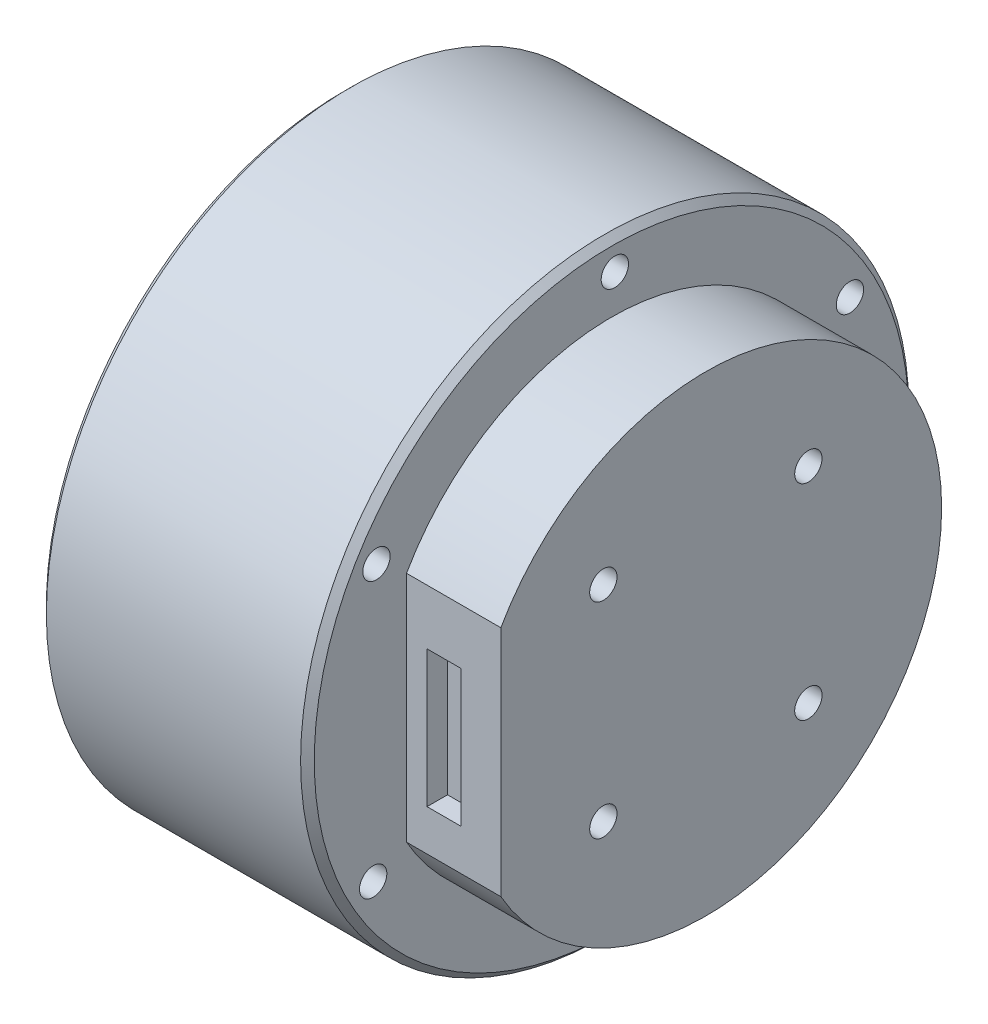
SolidWorks part; units mm, degrees
material "6061 合金"
ref_plane "前视基准面" through (0, 0, 0) normal (0, 0, 1) x (1, 0, 0)
ref_plane "上视基准面" through (0, 0, 0) normal (0, 1, 0) x (1, 0, 0)
ref_plane "右视基准面" through (0, 0, 0) normal (1, 0, 0) x (0, 0, -1)
other "Configuration Table"
sketch "草图1" plane through (0, 0, 0) normal (1, 0, 0) x (0, 0, -1)
  circle A0 centre (0, 0) radius 44.5
  dimension "D1" = 89
extrude "凸台-拉伸1" add sketch "草图1" along normal blind 39.2
sketch "草图2" plane through (39.2, 0, 0) normal (1, 0, 0) x (0, 0, -1)
  line L0 (-30, 17.0367) -> (-30, -17.0367)
  arc A0 (-30, -17.0367) -> (-30, 17.0367) centre (0, 0) ccw
  dimension "D1" = 69
  dimension "D2" = 30
extrude "凸台-拉伸3" add sketch "草图2" along normal blind 13.8
sketch "草图4" plane through (39.2, 0, 0) normal (1, 0, 0) x (0, 0, -1)
  circle A0 centre (0, 0) radius 40 construction
  circle A1 centre (0.4843, 39.9971) radius 2
  circle A2 centre (34.8806, 19.5791) radius 2
  circle A3 centre (34.3963, -20.418) radius 2
  circle A4 centre (-0.4843, -39.9971) radius 2
  circle A5 centre (-34.8806, -19.5791) radius 2
  circle A6 centre (-34.3963, 20.418) radius 2
  point P17 (0, 0)
  dimension "D1" = 80
  dimension "D2" = 4
  dimension "D3" = 6
extrude "切除-拉伸1" cut sketch "草图4" against normal blind 13.8
sketch "草图5" plane through (53, 0, 0) normal (1, 0, 0) x (0, 0, -1)
  line L1 (-15, 15) -> (-15, -15) construction
  line L2 (-15, -15) -> (15, -15) construction
  line L3 (15, -15) -> (15, 15) construction
  line L4 (15, 15) -> (-15, 15) construction
  circle A0 centre (0, 0) radius 15 construction
  circle A1 centre (-15, 15) radius 2
  circle A2 centre (15, 15) radius 2
  circle A3 centre (15, -15) radius 2
  circle A4 centre (-15, -15) radius 2
  dimension "D2" = 4
  dimension "D1" = 30
extrude "切除-拉伸2" cut sketch "草图5" against normal blind 10
chamfer "倒角1" distance 1 angle 45 2 edges at (39.2, 0, -44.5) (0, 0, -44.5)
sketch "草图6" plane through (0, 0, 0) normal (-1, 0, 0) x (0, 0, 1)
  line L0 (0, 22) -> (0, 0) construction
  line L1 (0, 0) -> (-12.3744, 12.3744) construction
  circle A0 centre (0, 0) radius 17.5 construction
  circle A1 centre (0, 0) radius 22 construction
  circle A2 centre (0, 22) radius 2.5
  circle A3 centre (-12.3744, 12.3744) radius 2.5
  circle A4 centre (22, 0) radius 2.5
  circle A5 centre (12.3744, 12.3744) radius 2.5
  circle A6 centre (0, -22) radius 2.5
  circle A7 centre (12.3744, -12.3744) radius 2.5
  circle A8 centre (-22, 0) radius 2.5
  circle A9 centre (-12.3744, -12.3744) radius 2.5
  point P23 (0, 0)
  dimension "D1" = 35
  dimension "D2" = 44
  dimension "D3" = 5
  dimension "D4" = 5
  dimension "D5" = 45
  dimension "D6" = 4
extrude "切除-拉伸3" cut sketch "草图6" against normal blind 5
sketch "草图7" plane through (0, 0, 30) normal (0, 0, 1) x (1, 0, 0)
  line L0 (53, -17.0367) -> (39.2, -17.0367) construction
  line L1 (42.2, 8.9633) -> (47.2, 8.9633)
  line L2 (42.2, 8.9633) -> (42.2, -11.0367)
  line L3 (42.2, -11.0367) -> (47.2, -11.0367)
  line L4 (47.2, 8.9633) -> (47.2, -11.0367)
  line L5 (39.2, -43.5) -> (39.2, 43.5) construction
  dimension "D1" = 5
  dimension "D2" = 20
  dimension "D3" = 6
  dimension "D4" = 3
extrude "切除-拉伸4" cut sketch "草图7" against normal blind 3
sketch "草图8" plane through (0, 0, 0) normal (-1, 0, 0) x (0, 0, 1)
  circle A0 centre (0, 0) radius 8.75
  dimension "D1" = 17.5
extrude "切除-拉伸5" cut sketch "草图8" against normal blind 17
